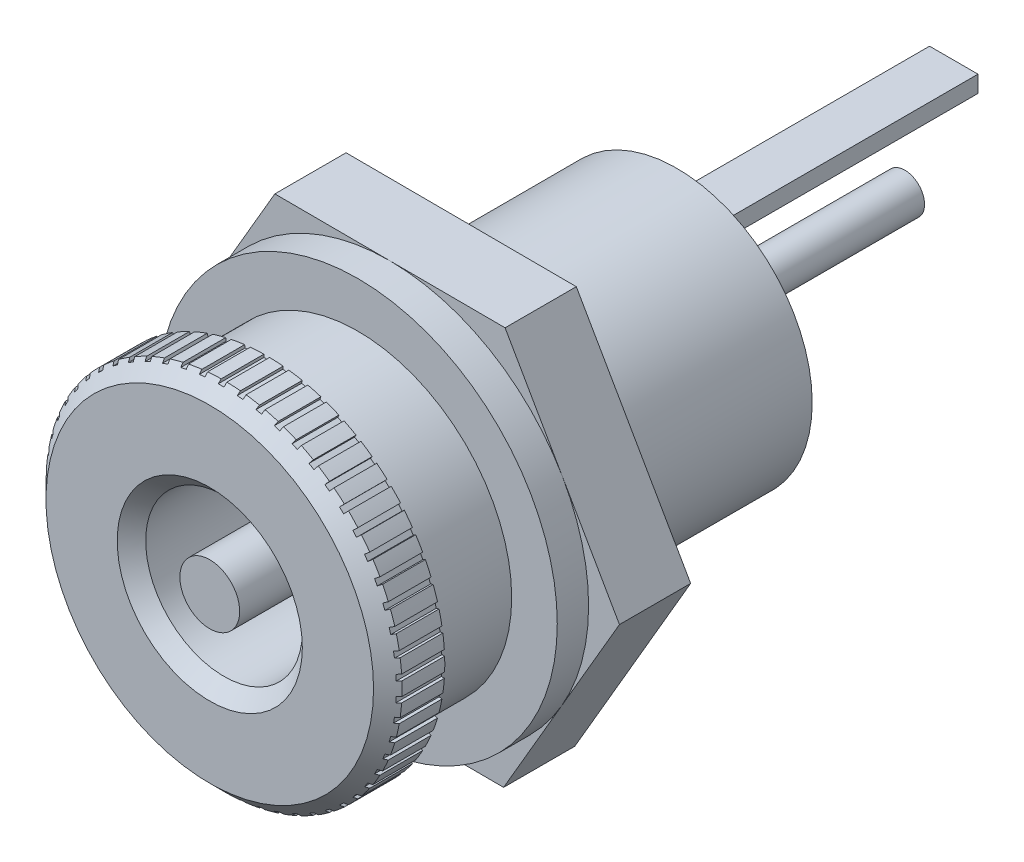
SolidWorks part; units mm, degrees
ref_plane "前视基准面" through (0, 0, 0) normal (0, 0, 1) x (1, 0, 0)
ref_plane "上视基准面" through (0, 0, 0) normal (0, 1, 0) x (1, 0, 0)
ref_plane "右视基准面" through (0, 0, 0) normal (1, 0, 0) x (0, 0, -1)
sketch "草图1" plane through (0, 0, 0) normal (0, 0, 1) x (1, 0, 0)
  circle A0 centre (0, 0) radius 6.25
  dimension "D1" = 12.5
extrude "凸台-拉伸1" add sketch "草图1" along normal blind 2
sketch "草图2" plane through (0, 0, 2) normal (0, 0, 1) x (1, 0, 0)
  circle A0 centre (0, 0) radius 4.75
  dimension "D1" = 9.5
extrude "凸台-拉伸2" add sketch "草图2" against normal blind 16.4
sketch "草图4" plane through (0, 0, -14.4) normal (0, 0, -1) x (-1, 0, 0)
  line L1 (-0.8703, 3.1977) -> (0.8312, 3.1977)
  line L2 (-0.8703, 3.1977) -> (-0.8703, 2.611)
  line L3 (-0.8703, 2.611) -> (0.8312, 2.611)
  line L4 (0.8312, 3.1977) -> (0.8312, 2.611)
extrude "凸台-拉伸3" add sketch "草图4" along normal blind 9.7
sketch "草图5" plane through (0, 0, -14.4) normal (0, 0, -1) x (-1, 0, 0)
  circle A0 centre (0, 0) radius 0.6949
extrude "凸台-拉伸4" add sketch "草图5" along normal blind 8
sketch "草图6" plane through (0, 0, 0) normal (0, 0, -1) x (-1, 0, 0)
  circle A0 centre (0, 0) radius 5.4
  dimension "D1" = 10.8
extrude "凸台-拉伸5" add sketch "草图6" along normal blind 7.8
sketch "草图3" plane through (0, 0, 2) normal (0, 0, 1) x (1, 0, 0)
  circle A0 centre (0, 0) radius 2.75
  circle A1 centre (0, 0) radius 1.05
  dimension "D1" = 5.5
  dimension "D2" = 2.1
extrude "切除-拉伸1" cut sketch "草图3" against normal blind 12
chamfer "倒角1" distance 0.5 angle 45 1 edges at (6.25, 0, 2)
chamfer "倒角2" distance 0.5 angle 45 1 edges at (2.75, 0, 2)
sketch "草图7" plane through (0, 0, 2) normal (0, 0, 1) x (1, 0, 0)
  line L0 (0, 0) -> (0, 10.4034) construction
  line L1 (-0.1, 7.1467) -> (0.1, 7.1467)
  line L2 (-0.1, 7.1467) -> (-0.1, 6.1489)
  line L3 (-0.1, 6.1489) -> (0.1, 6.1489)
  line L4 (0.1, 7.1467) -> (0.1, 6.1489)
  dimension "D1" = 0.2
extrude "切除-拉伸2" cut sketch "草图7" against normal through all
pattern_circular "阵列(圆周)1" count 58 over 360 about axis through (0, 0, 0) along (0, 0, 1) of "切除-拉伸2"
ref_plane "基准面1" through (0, 0, -6.8) normal (0, 0, -1) x (-1, 0, 0)
sketch "草图8" plane through (0, 0, -6.8) normal (0, 0, -1) x (-1, 0, 0)
  line L1 (-4.0677, 6.9848) -> (-8.0828, -0.0303)
  line L2 (-8.0828, -0.0303) -> (-4.0151, -7.0151)
  line L3 (-4.0151, -7.0151) -> (4.0677, -6.9848)
  line L4 (4.0677, -6.9848) -> (8.0828, 0.0303)
  line L5 (8.0828, 0.0303) -> (4.0151, 7.0151)
  line L6 (4.0151, 7.0151) -> (-4.0677, 6.9848)
  circle A0 centre (0, 0) radius 7 construction
  dimension "D1" = 14
extrude "凸台-拉伸6" add sketch "草图8" against normal blind 2.5
sketch "草图9" plane through (0, 0, -4.3) normal (0, 0, 1) x (1, 0, 0)
  circle A0 centre (0, 0) radius 7
  dimension "D1" = 14
extrude "凸台-拉伸7" add sketch "草图9" along normal blind 1.1
